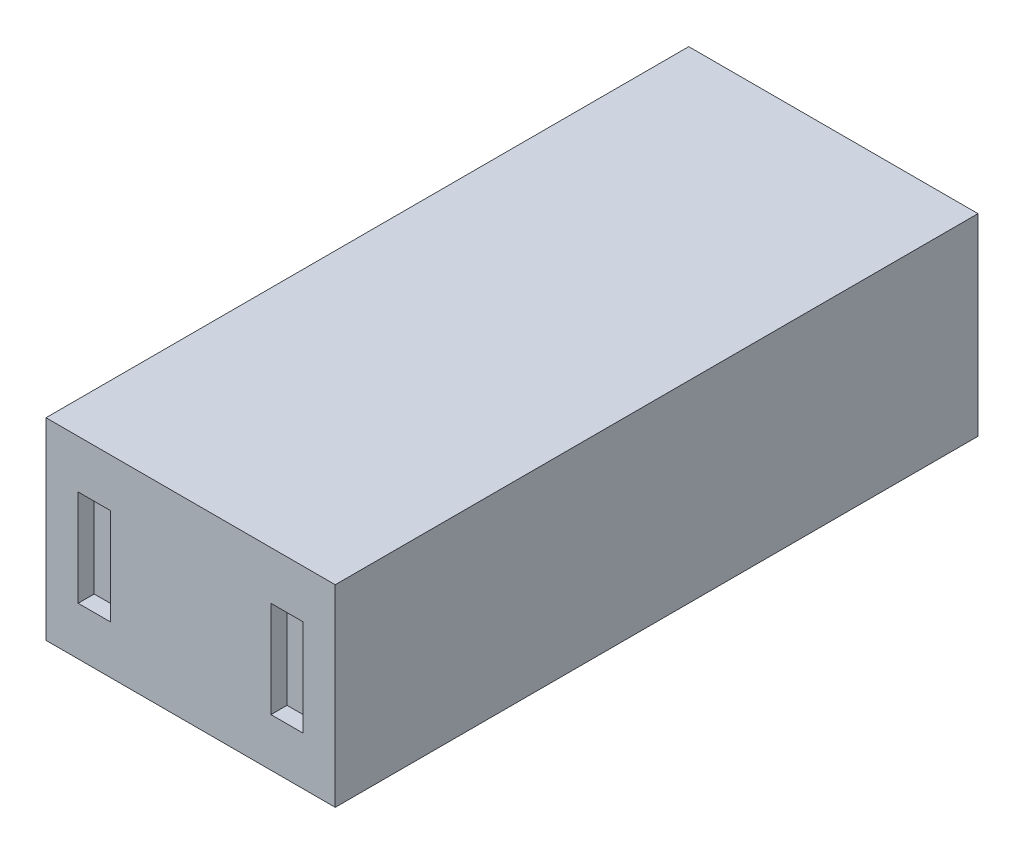
SolidWorks part; units mm, degrees
ref_plane "Спереди" through (0, 0, 0) normal (0, 0, 1) x (1, 0, 0)
ref_plane "Сверху" through (0, 0, 0) normal (0, 1, 0) x (1, 0, 0)
ref_plane "Справа" through (0, 0, 0) normal (1, 0, 0) x (0, 0, -1)
other "Configuration Table"
sketch "Эскиз1" plane through (0, 0, 0) normal (0, 0, 1) x (1, 0, 0)
  line L1 (-45, -30) -> (45, -30)
  line L2 (-45, -30) -> (-45, 30)
  line L3 (-45, 30) -> (45, 30)
  line L4 (45, -30) -> (45, 30)
  line L5 (-45, -30) -> (45, 30) construction
  line L6 (-45, 30) -> (45, -30) construction
  point P0 (0, 0)
  dimension "D1" = 60
  dimension "D2" = 90
extrude "Бобышка-Вытянуть1" add sketch "Эскиз1" along normal mid plane 200
sketch "Эскиз2" plane through (0, 0, 100) normal (0, 0, 1) x (1, 0, 0)
  line L0 (-1000, 0) -> (49000, 0) construction
  line L1 (0, -1000) -> (0, 49000) construction
  line L2 (35, 15) -> (25, -15) construction
  line L3 (-35, -15) -> (-25, -15)
  line L4 (-35, -15) -> (-35, 15)
  line L5 (-35, 15) -> (-25, 15)
  line L6 (-25, -15) -> (-25, 15)
  line L7 (-35, -15) -> (-25, 15) construction
  line L8 (-35, 15) -> (-25, -15) construction
  line L9 (35, -15) -> (25, 15) construction
  line L10 (25, -15) -> (25, 15)
  line L11 (35, 15) -> (25, 15)
  line L12 (35, -15) -> (35, 15)
  line L13 (35, -15) -> (25, -15)
  point P4 (-30, 0)
  point P14 (30, 0)
  dimension "D1" = 30
  dimension "D2" = 10
  dimension "D3" = 25
extrude "Вырез-Вытянуть1" cut sketch "Эскиз2" against normal blind 5
